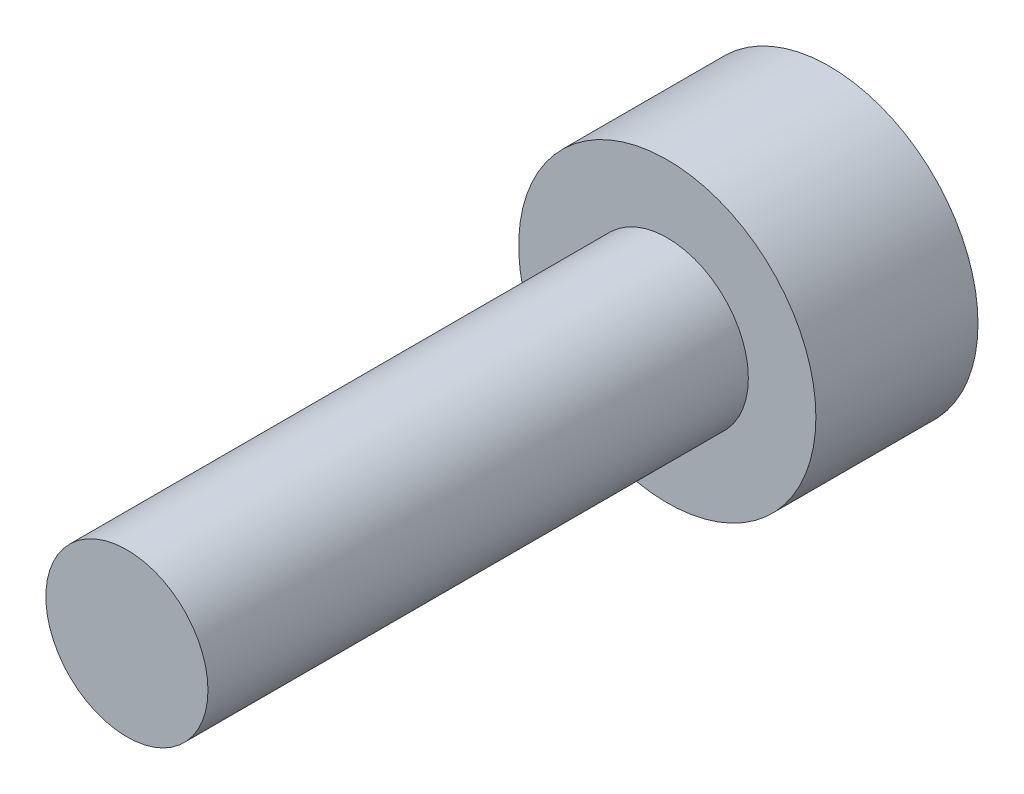
SolidWorks part; units mm, degrees
material "AISI 4340 Steel, normalized"
ref_plane "Front Plane" through (0, 0, 0) normal (0, 0, 1) x (1, 0, 0)
ref_plane "Top Plane" through (0, 0, 0) normal (0, 1, 0) x (1, 0, 0)
ref_plane "Right Plane" through (0, 0, 0) normal (1, 0, 0) x (0, 0, -1)
sketch "Sketch1" plane through (0, 0, 0) normal (0, 0, 1) x (1, 0, 0)
  circle A0 centre (0, 0) radius 2.75
extrude "Head_Envelope" add sketch "Sketch1" along normal blind 3 from offset 3
sketch "Sketch2" plane through (0, 0, 0) normal (0, 0, 1) x (1, 0, 0)
  circle A0 centre (0, 0) radius 1.5
extrude "Thread_Major_Envelope" add sketch "Sketch2" along normal blind 10
